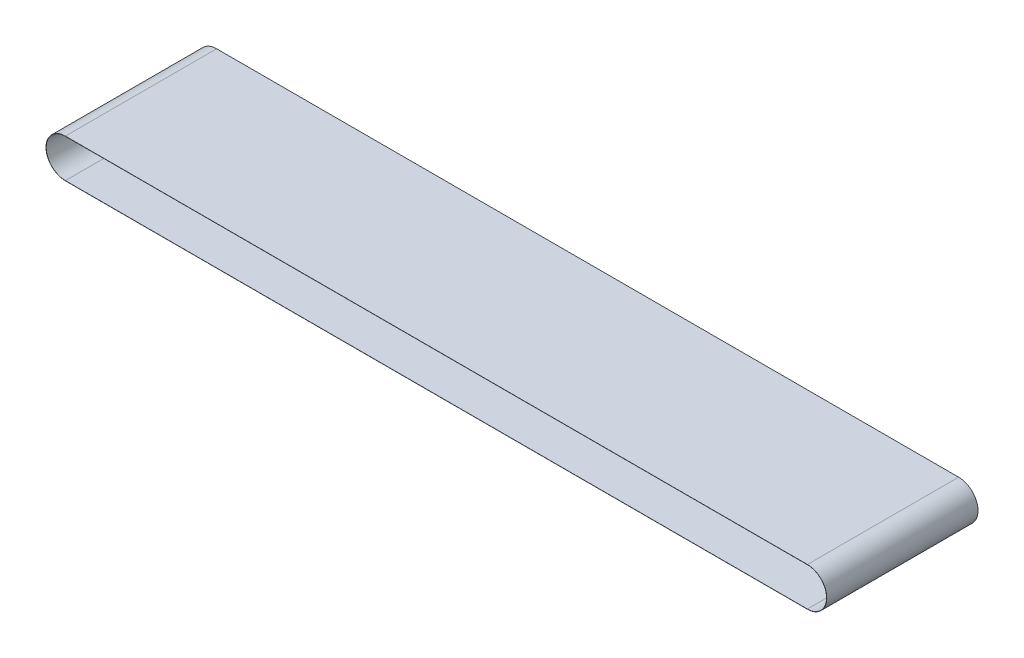
SolidWorks part; units mm, degrees
ref_plane "前视基准面" through (0, 0, 0) normal (0, 0, 1) x (1, 0, 0)
ref_plane "上视基准面" through (0, 0, 0) normal (0, 1, 0) x (1, 0, 0)
ref_plane "右视基准面" through (0, 0, 0) normal (1, 0, 0) x (0, 0, -1)
sketch "草图1" plane through (0, 0, 0) normal (0, 0, 1) x (1, 0, 0)
  line L0 (0, 0) -> (392.5, 0) construction
  line L1 (0, 10.25) -> (392.5, 10.25)
  line L2 (0, -10.25) -> (392.5, -10.25)
  line L3 (0, 10.15) -> (392.5, 10.15)
  line L4 (0, -10.15) -> (392.5, -10.15)
  arc A0 (0, 10.25) -> (0, -10.25) centre (0, 0) ccw
  arc A1 (392.5, -10.25) -> (392.5, 10.25) centre (392.5, 0) ccw
  arc A2 (392.5, -10.15) -> (392.5, 10.15) centre (392.5, 0) ccw
  arc A3 (0, 10.15) -> (0, -10.15) centre (0, 0) ccw
  point P3 (196.25, 0)
  point P8 (402.75, 0)
  point P9 (-10.25, 0)
  dimension "D1" = 413
  dimension "D2" = 20.5
  dimension "D3" = 0.1
extrude "凸台-拉伸1" add sketch "草图1" along normal blind 80
